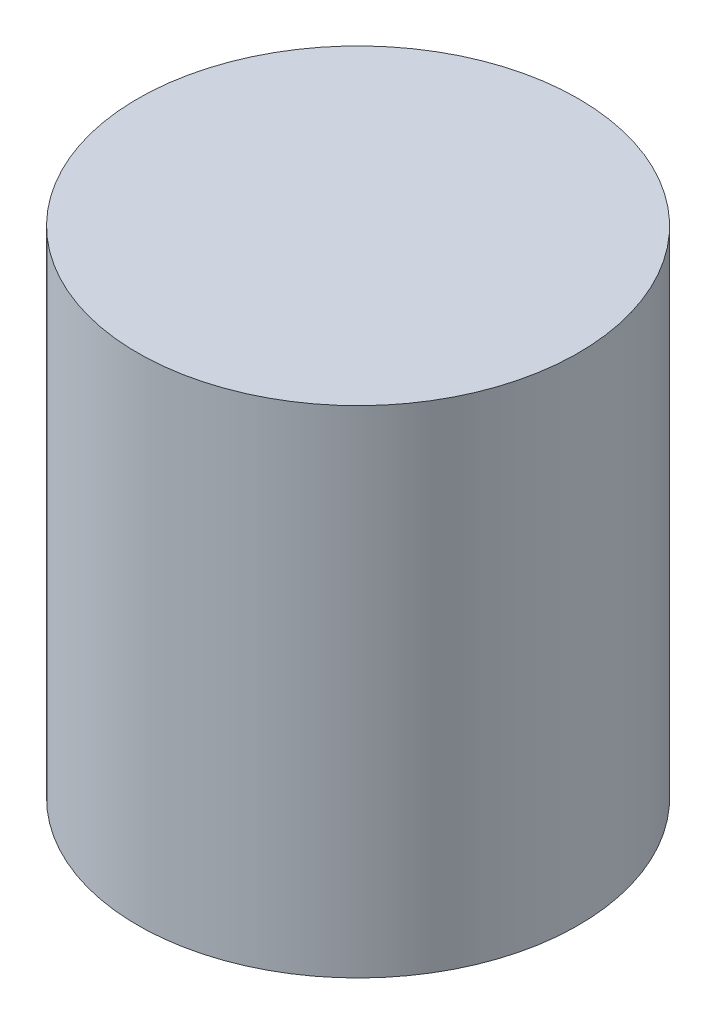
SolidWorks part; units mm, degrees
ref_plane "Front Plane" through (0, 0, 0) normal (0, 0, 1) x (1, 0, 0)
ref_plane "Top Plane" through (0, 0, 0) normal (0, 1, 0) x (1, 0, 0)
ref_plane "Right Plane" through (0, 0, 0) normal (1, 0, 0) x (0, 0, -1)
sketch "Sketch1" plane through (0, 0, 0) normal (0, 1, 0) x (1, 0, 0)
  circle A0 centre (0, 0) radius 20
  dimension "D1" = 40
extrude "Boss-Extrude1" add sketch "Sketch1" along normal blind 45
